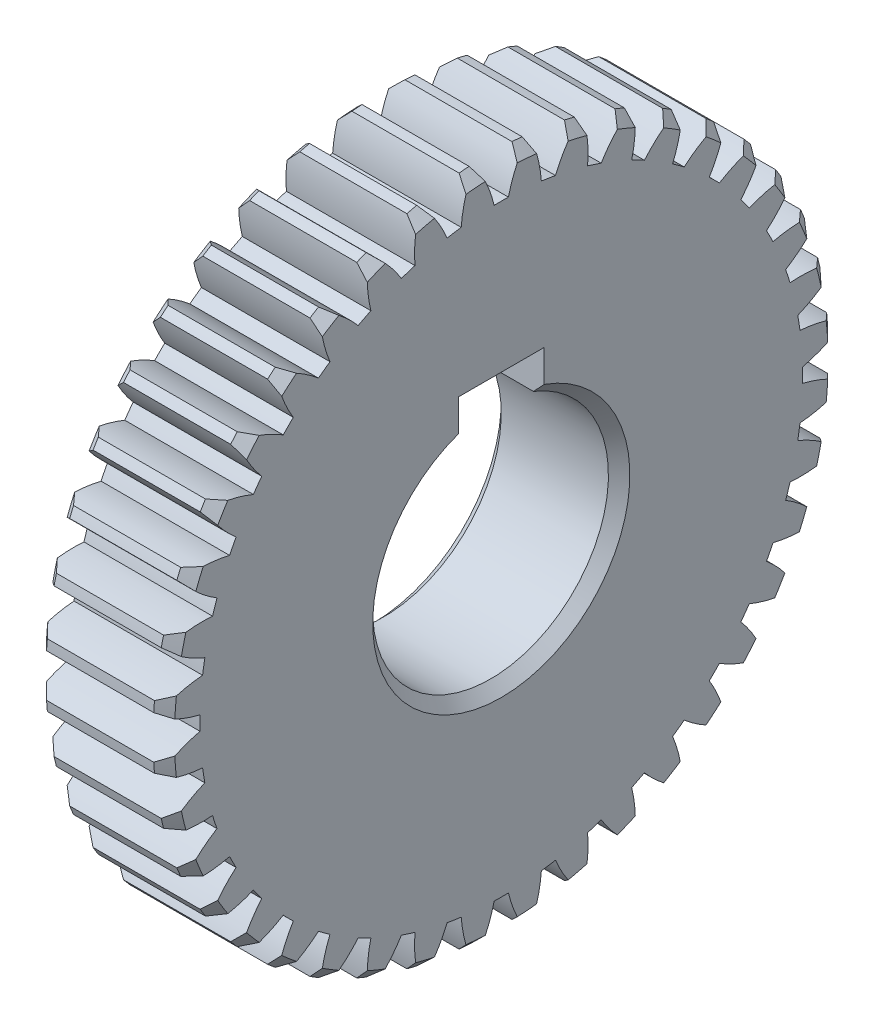
SolidWorks part; units mm, degrees
ref_plane "Plane1" through (0, 0, 0) normal (0, 0, 1) x (1, 0, 0)
ref_plane "Plane2" through (0, 0, 0) normal (0, 1, 0) x (1, 0, 0)
ref_plane "Plane3" through (0, 0, 0) normal (1, 0, 0) x (0, 0, -1)
sketch "HoldingSke" plane through (0, 0, 0) normal (0, 1, 0) x (1, 0, 0)
  line L0 (0, 0) -> (0.5107, -0.4285)
  line L1 (-15, 0) -> (100, 0) construction
  line L2 (0, 0) -> (-2.1039, 2.3779)
  line L3 (0, 0) -> (-11.863, 4.5341)
  line L4 (0, 0) -> (6.6156, 5.5511)
  line L5 (0, 0) -> (-46.8476, -17.4728)
  line L6 (0, 0) -> (-9.9476, -6.7116)
  line L7 (-2.1039, 2.3779) -> (8.6586, 51.2059)
  line L8 (-76.2, 54.61) -> (-72.9, 54.61)
  line L9 (-71.009, 38.7566) -> (-53.1078, 45.2721)
  line L10 (-76.2, 71.12) -> (104.1128, 71.12)
  line L11 (0, 0) -> (-12, 0)
  line L12 (-76.2, 101.6) -> (-76.147, 101.6)
  line L13 (24.9733, 27.94) -> (52.9518, 28.4284)
  line L14 (24.9733, 27.94) -> (24.9743, 27.94)
  line L15 (24.9733, 27.94) -> (100.4006, 29.5858)
  line L16 (-63.627, -1.5) -> (-12.827, -1.5)
  circle A0 centre (0, 0) radius 11
  circle A1 centre (0, 0) radius 28.124
  circle A2 centre (0, 0) radius 37.5
  circle A3 centre (0, 0) radius 11
  dimension "MHD" = 56.248
  dimension "Hub_dia" = 75
  dimension "Bore" = 22
  dimension "MBD" = 22
  dimension "Num_teeth" = 40
  dimension "Pitch" = 0.6667
  dimension "Overall_len" = 50
  dimension "Show_teeth" = 40
  dimension "Thickness" = 12
  dimension "OAL" = 50.0001
  dimension "T_dim" = 3.3
  dimension "Ap" = 20
  dimension "H" = 19.05
  dimension "Pitch_radius" = 180.3128
  dimension "Width" = 12
  dimension "Backlash" = 0.053
  dimension "Addendum_fac" = 1
  dimension "Dedendum_fac" = 1.25
  dimension "Clearance_fac" = 0.25
  dimension "Dedendum_add" = 0.001
  dimension "Module" = 1.5
sketch "BasProSke" plane through (0, 0, 0) normal (0, 1, 0) x (1, 0, 0)
  line L0 (-10, 0) -> (60, 0) construction
  line L1 (0, 0) -> (0, 31.5)
  line L2 (0, 0) -> (12, 0)
  line L3 (12, 0) -> (12, 31.5)
  line L4 (12, 31.5) -> (0, 31.5)
  dimension "Thickness" = 12
  dimension "Diameter" = 63
revolve "Base-Revolve" add sketch "BasProSke" angle 360 about L0
sketch "TooCutSke" plane through (0, 0, 0) normal (1, 0, 0) x (0, 0, -1)
  line L1 (0, 0) -> (0, 107) construction
  line L2 (0, 0) -> (-1.2705, 29.9731) construction
  line L3 (0, 0) -> (-4.7045, 59.7759) construction
  line L4 (-1.2705, 29.9731) -> (-2.3522, 29.888) construction
  arc A0 (0.6666, 28.1161) -> (-0.6666, 28.1161) centre (0, 0) ccw
  arc A1 (2.0175, 31.4608) -> (-2.0175, 31.4608) centre (0, 0) ccw
  circle A2 centre (0, 0) radius 30 construction
  circle A3 centre (0, 0) radius 28.1908 construction
  arc A4 (-0.6666, 28.1161) -> (-2.0175, 31.4608) centre (-12.3423, 25.3454) ccw
  arc A5 (2.0175, 31.4608) -> (0.6666, 28.1161) centre (12.3423, 25.3454) ccw
  dimension "Root_dia" = 56.248
  dimension "Overcut_dia" = 63.0508
  dimension "Pitch_dia" = 60
  dimension "Base_dia" = 56.3816
  dimension "Flank_rad" = 12
  dimension "Half_ang" = 4.5
  dimension "Half_CT" = 1.085
extrude "ToothCut" cut sketch "TooCutSke" along normal through all
fillet "Breaks" [suppressed] radius 0.03
fillet "RootFillets" [suppressed] radius 0.376
pattern_circular "TeethCuts" count 40 every 9 about axis through (-10, 0, 0) along (1, 0, 0) of "ToothCut", "RootFillets", "Breaks"
sketch "HubNeaOneSke" plane through (0, 0, 0) normal (-1, 0, 0) x (0, 0, 1)
  circle A0 centre (0, 0) radius 28.124
  dimension "Diameter" = 56.248
extrude "HubNearOne" [suppressed] add sketch "HubNeaOneSke" along normal blind 38.0001
sketch "HubNeaBotSke" plane through (0, 0, 0) normal (-1, 0, 0) x (0, 0, 1)
  circle A0 centre (0, 0) radius 28.124
  dimension "Diameter" = 56.248
extrude "HubNearBoth" [suppressed] add sketch "HubNeaBotSke" along normal blind 19
ref_plane "FarPln" through (12, 0, 0) normal (1, 0, 0) x (0, 0, -1)
sketch "HubFarSke" plane through (12, 0, 0) normal (1, 0, 0) x (0, 0, -1)
  circle A0 centre (0, 0) radius 28.124
  dimension "Diameter" = 56.248
extrude "HubFar" [suppressed] add sketch "HubFarSke" along normal blind 19
sketch "BorSke" plane through (0, 0, 0) normal (1, 0, 0) x (0, 0, -1)
  circle A0 centre (0, 0) radius 11
  dimension "Diameter" = 22
extrude "Bore" cut sketch "BorSke" along normal mid plane 100.0001
sketch "KeySke" plane through (0, 0, 0) normal (1, 0, 0) x (0, 0, -1)
  line L0 (-4, 0) -> (-4, 14.3)
  line L1 (-4, 14.3) -> (4, 14.3)
  line L2 (4, 14.3) -> (4, 0)
  line L3 (0, 0) -> (0, 34) construction
  line L4 (-4, 0) -> (4, 0)
  dimension "Offset" = 14.3
  dimension "Width" = 8
extrude "Keyway" cut sketch "KeySke" along normal mid plane 100.0001
pattern_circular "Keyway2" [suppressed] count 2 every 90 about axis through (-10, 0, 0) along (1, 0, 0)
chamfer "Chamfer1" distance 1 angle 45 82 edges at (0, -11, 0) (12, -30.6297, -7.3535) (12, -29.1022, -12.0545) (12, -26.8582, -16.4587) (12, -23.9528, -20.4576) (12, -20.4576, -23.9528) (12, -31.4029, -2.4715) (12, -31.4029, 2.4715) (12, -30.6297, 7.3535) (12, -29.1022, 12.0545) (12, -26.8582, 16.4587) (12, -23.9528, 20.4576) (12, -20.4576, 23.9528) (12, -16.4587, 26.8582) (12, -12.0545, 29.1022) (12, -7.3535, 30.6297) (12, -2.4715, 31.4029) (12, 2.4715, 31.4029) (12, 7.3535, 30.6297) (12, 12.0545, 29.1022) (12, 16.4587, 26.8582) (12, 20.4576, 23.9528) (12, 23.9528, 20.4576) (12, 26.8582, 16.4587) (12, 29.1022, 12.0545) (12, 30.6297, 7.3535) (12, 31.4029, 2.4715) (12, 31.4029, -2.4715) (12, 30.6297, -7.3535) (12, 29.1022, -12.0545) (12, 26.8582, -16.4587) (12, 23.9528, -20.4576) (12, 20.4576, -23.9528) (12, 16.4587, -26.8582) (12, 12.0545, -29.1022) (12, -16.4587, -26.8582) (12, -12.0545, -29.1022) (12, -7.3535, -30.6297) (12, -2.4715, -31.4029) (12, 2.4715, -31.4029) (12, 7.3535, -30.6297) (0, 16.4587, 26.8582) (0, 20.4576, 23.9528) (0, 23.9528, 20.4576) (0, 26.8582, 16.4587) (0, 29.1022, 12.0545) (0, 30.6297, 7.3535) (0, 31.4029, 2.4715) (0, 31.4029, -2.4715) (0, 30.6297, -7.3535) (0, 29.1022, -12.0545) (0, 26.8582, -16.4587) (0, 12.0545, 29.1022) (0, 7.3535, 30.6297) (0, 2.4715, 31.4029) (0, -2.4715, 31.4029) (0, -7.3535, 30.6297) (0, -12.0545, 29.1022) (0, -16.4587, 26.8582) (0, -20.4576, 23.9528) (0, -23.9528, 20.4576) (0, -26.8582, 16.4587) (0, -29.1022, 12.0545) (0, -30.6297, 7.3535) (0, -31.4029, 2.4715) (0, -31.4029, -2.4715) (0, -30.6297, -7.3535) (0, -29.1022, -12.0545) (0, -26.8582, -16.4587) (0, -23.9528, -20.4576) (0, -20.4576, -23.9528) (0, -16.4587, -26.8582) (0, -12.0545, -29.1022) (0, -7.3535, -30.6297) (0, -2.4715, -31.4029) (0, 2.4715, -31.4029) (0, 7.3535, -30.6297) (0, 12.0545, -29.1022) (0, 16.4587, -26.8582) (0, 20.4576, -23.9528) (0, 23.9528, -20.4576) (12, -11, 0)
equation "' \"Module@HoldingSke\" = 6.35"
equation "' \"Num_teeth@HoldingSke\" = 12"
equation "' \"Ap@HoldingSke\" =  20"
equation "' \"Ap@HoldingSke\" = 20"
equation "' \"Width@HoldingSke\" = 0.5 * 25.4"
equation "' \"Hub_dia@HoldingSke\"= 1 * 25.4"
equation "' \"Hub_dia@HoldingSke\" = 1 * 25.4"
equation "' \"Overall_len@HoldingSke\" = 1.0 * 25.4"
equation "' \"Bore@HoldingSke\" = 0.75 * 25.4"
equation "' \"T_dim@HoldingSke\" = 0.1 * 25.4"
equation "' \"Width@KeySke\" = 0.25 * 25.4"
equation "' \"Show_teeth@HoldingSke\" = 13"
equation "' \"Backlash@HoldingSke\" = 0.009 * 25.4"
equation "' \"Addendum_fac@HoldingSke\" = 1.0"
equation "' \"Dedendum_fac@HoldingSke\" = 1.25"
equation "' \"Dedendum_add@HoldingSke\" = 0.00005 * 25.4"
equation "' \"Clearance_fac@HoldingSke\" = 0.25"
equation "\"Pitch@HoldingSke\" = 1 / \"Module@HoldingSke\""
equation "\"Overcut_dia@TooCutSke\" = (\"Num_teeth@HoldingSke\" + 2 * \"Addendum_fac@HoldingSke\") / \"Pitch@HoldingSke\" + 0.002 * 25.4"
equation "\"Pitch_dia@TooCutSke\" = \"Num_teeth@HoldingSke\" / \"Pitch@HoldingSke\""
equation "\"Base_dia@TooCutSke\" = \"Num_teeth@HoldingSke\" / \"Pitch@HoldingSke\" * cos((\"Ap@HoldingSke\"  * 3.14159265 / 180))"
equation "\"Root_dia@TooCutSke\" = (\"Num_teeth@HoldingSke\" + 2) / \"Pitch@HoldingSke\" - 2 * (\"Addendum_fac@HoldingSke\" + \"Dedendum_fac@HoldingSke\") / \"Pitch@HoldingSke\" - \"Dedendum_add@HoldingSke\" * 2"
equation "\"Half_ang@TooCutSke\" = 180 / \"Num_teeth@HoldingSke\""
equation "\"Half_CT@TooCutSke\" = \"Num_teeth@HoldingSke\" / \"Pitch@HoldingSke\" * sin((3.14159265 / 2 / \"Num_teeth@HoldingSke\")) / 2 - 7 * \"Backlash@HoldingSke\" / 4"
equation "\"Flank_rad@TooCutSke\" = \"Num_teeth@HoldingSke\" / \"Pitch@HoldingSke\" / 5"
equation "\"Radius@RootFillets\" = \"Clearance_fac@HoldingSke\" / \"Pitch@HoldingSke\" + \"Dedendum_add@HoldingSke\""
equation "\"Break_rad@Breaks\" = 0.02 / \"Pitch@HoldingSke\""
equation "\"Thickness@HoldingSke\" = \"Width@HoldingSke\""
equation "\"OAL@HoldingSke\" = \"Thickness@HoldingSke\""
equation "\"MHD@HoldingSke\" = (\"Num_teeth@HoldingSke\" + 2) / \"Pitch@HoldingSke\" - 2 * (\"Addendum_fac@HoldingSke\" + \"Dedendum_fac@HoldingSke\")  / \"Pitch@HoldingSke\" - \"Dedendum_add@HoldingSke\" * 2"
equation "\"MBD@HoldingSke\" = (\"Num_teeth@HoldingSke\" + 2) / \"Pitch@HoldingSke\" - 2 * (\"Addendum_fac@HoldingSke\" + \"Dedendum_fac@HoldingSke\")  / \"Pitch@HoldingSke\" - \"Dedendum_add@HoldingSke\" * 2 - 0.002 * 25.4"
equation "\"MHD@HoldingSke\" = ((sgn( \"MHD@HoldingSke\" - \"Hub_dia@HoldingSke\" )-1)*( \"MHD@HoldingSke\" - \"Hub_dia@HoldingSke\" ))/-2+ \"Hub_dia@HoldingSke\""
equation "\"MBD@HoldingSke\" = ((sgn( \"MBD@HoldingSke\" - \"Bore@HoldingSke\" )-1)*( \"MBD@HoldingSke\" - \"Bore@HoldingSke\" ))/-2+ \"Bore@HoldingSke\""
equation "\"OAL@HoldingSke\" = ((sgn( \"OAL@HoldingSke\" - \"Overall_len@HoldingSke\" )+1)*( \"OAL@HoldingSke\" - \"Overall_len@HoldingSke\" ))/2 + \"Overall_len@HoldingSke\" + 0.000002 * 25.4"
equation "\"Num_teeth@TeethCuts\" = int( \"Show_teeth@HoldingSke\" ) + 1"
equation "\"Num_teeth@TeethCuts\" = ((sgn( \"Num_teeth@TeethCuts\" - \"Num_teeth@HoldingSke\" )-1)*( \"Num_teeth@TeethCuts\" - \"Num_teeth@HoldingSke\" ))/-2+ \"Num_teeth@HoldingSke\""
equation "\"Num_teeth@TeethCuts\" = ((sgn( \"Num_teeth@TeethCuts\" - 2.0)+1)*( \"Num_teeth@TeethCuts\" - 2.0))/2 +2.0"
equation "\"Angle@TeethCuts\" = 360.0 / \"Num_teeth@HoldingSke\""
equation "\"Diameter@BasProSke\" = (\"Num_teeth@HoldingSke\" + 2 * \"Addendum_fac@HoldingSke\") / \"Pitch@HoldingSke\""
equation "\"Thickness@BasProSke\"  = \"Thickness@HoldingSke\""
equation "' \"Fillet_rad@BasProSke\" =  \"Thickness@HoldingSke\" * 0.05"
equation "' \"Fillet_rad@BasProSke\" = \"Thickness@HoldingSke\" * 0.05"
equation "\"MHD@HoldingSke\" = ((sgn( \"MHD@HoldingSke\" - \"Root_dia@TooCutSke\" )-1)*( \"MHD@HoldingSke\" - \"Root_dia@TooCutSke\" ))/-2+ \"Root_dia@TooCutSke\""
equation "\"Diameter@HubNeaOneSke\" = \"MHD@HoldingSke\""
equation "\"Length@HubNearOne\" = \"OAL@HoldingSke\" - \"Thickness@BasProSke\""
equation "\"Diameter@HubNeaBotSke\" = \"MHD@HoldingSke\""
equation "\"Length@HubNearBoth\" = ( \"OAL@HoldingSke\" - \"Thickness@BasProSke\" ) / 2.0"
equation "\"Thickness@FarPln\" = \"Thickness@BasProSke\""
equation "\"Diameter@HubFarSke\" = \"MHD@HoldingSke\""
equation "\"Length@HubFar\" = ( \"OAL@HoldingSke\" - \"Thickness@BasProSke\" ) / 2.0"
equation "\"Diameter@BorSke\" = \"MBD@HoldingSke\""
equation "\"D1@Bore\" = \"OAL@HoldingSke\" * 2.0"
equation "\"D1@Keyway\" = \"OAL@HoldingSke\" * 2.0"
equation "\"Offset@KeySke\" = \"T_dim@HoldingSke\" + \"MBD@HoldingSke\" / 2.0"
